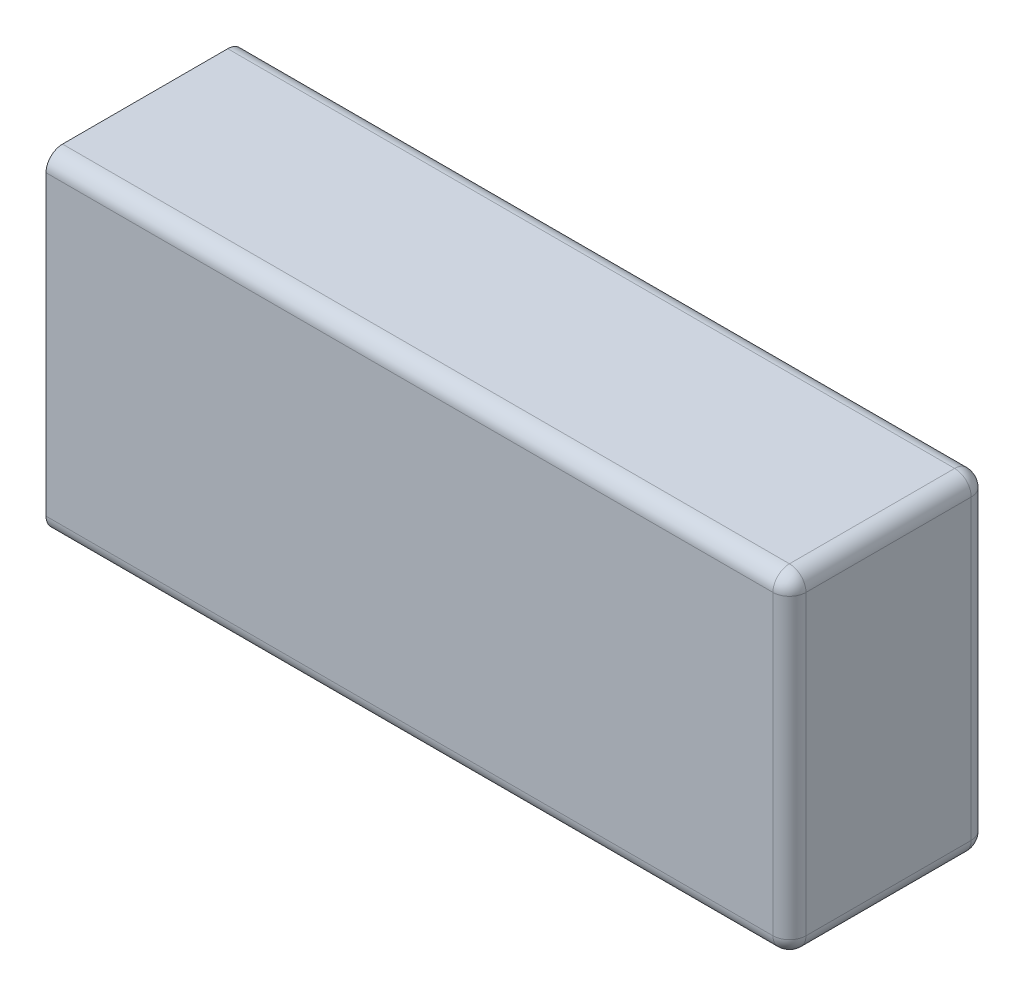
SolidWorks part; units mm, degrees
material "AISI 1020"
ref_plane "Спереди" through (0, 0, 0) normal (0, 0, 1) x (1, 0, 0)
ref_plane "Сверху" through (0, 0, 0) normal (0, 1, 0) x (1, 0, 0)
ref_plane "Справа" through (0, 0, 0) normal (1, 0, 0) x (0, 0, -1)
sketch "Эскиз1" plane through (0, 0, 0) normal (1, 0, 0) x (0, 0, -1)
  line L0 (-12.4891, 0) -> (11.7717, 0) construction
  line L1 (0, 11.0217) -> (0, -10.663) construction
  line L2 (-6, -9) -> (-6, 9)
  line L3 (-5, 10) -> (5, 10)
  line L4 (6, -9) -> (6, 9)
  line L5 (-5, -10) -> (5, -10)
  arc A0 (-6, 9) -> (-5, 10) centre (-5, 9) cw
  arc A1 (6, 9) -> (5, 10) centre (5, 9) ccw
  arc A2 (6, -9) -> (5, -10) centre (5, -9) cw
  arc A3 (-6, -9) -> (-5, -10) centre (-5, -9) ccw
  point P14 (0, 10)
  point P15 (6, 0)
  point P20 (-6, 0)
  dimension "D3" = 1
  dimension "D1" = 6
  dimension "D2" = 10
extrude "Бобышка-Вытянуть1" add sketch "Эскиз1" along normal blind 45
fillet "Скругление1" radius 1 8 edges at (45, 9.7071, 5.7071) (45, 10, 0) (45, 9.7071, -5.7071) (45, 0, -6) (45, -9.7071, -5.7071) (45, -10, 0) (45, -9.7071, 5.7071) (45, 0, 6)
